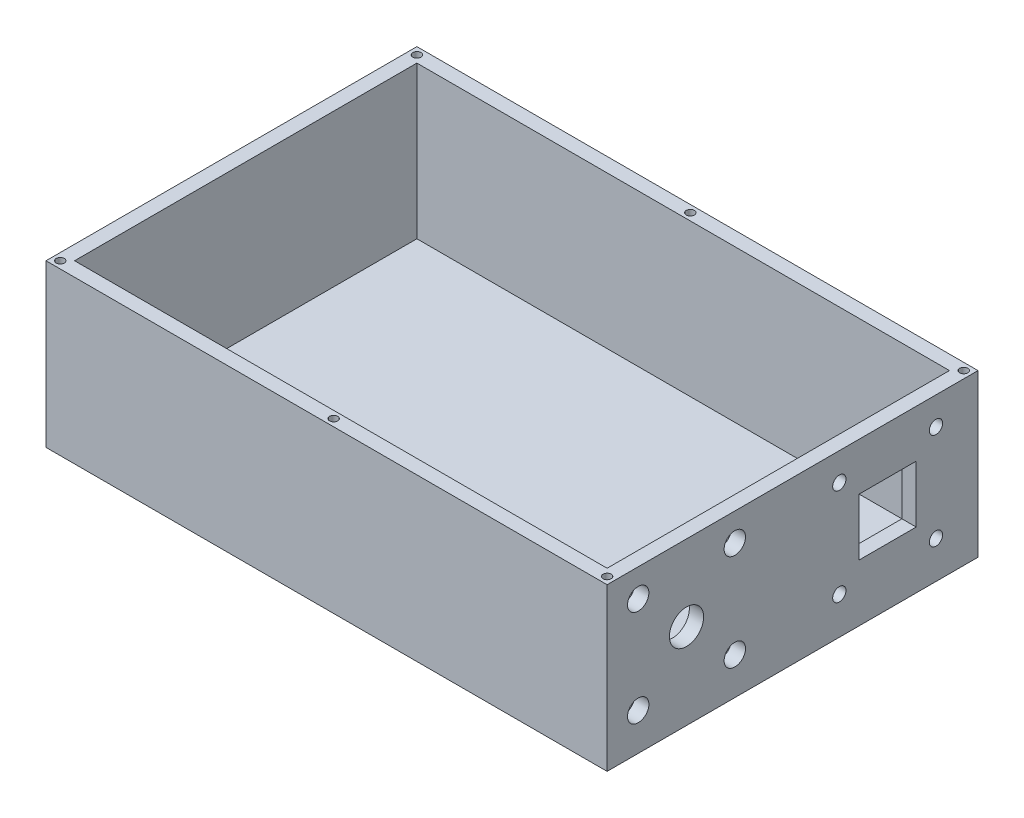
SolidWorks part; units mm, degrees
ref_plane "Front Plane" through (0, 0, 0) normal (0, 0, 1) x (1, 0, 0)
ref_plane "Top Plane" through (0, 0, 0) normal (0, 1, 0) x (1, 0, 0)
ref_plane "Right Plane" through (0, 0, 0) normal (1, 0, 0) x (0, 0, -1)
sketch "Sketch1" plane through (0, 0, 0) normal (0, 1, 0) x (1, 0, 0)
  line L1 (-59, 39) -> (59, 39)
  line L2 (-59, 39) -> (-59, -39)
  line L3 (-59, -39) -> (59, -39)
  line L4 (59, 39) -> (59, -39)
  line L5 (-59, 39) -> (59, -39) construction
  line L6 (-59, -39) -> (59, 39) construction
  point P0 (0, 0)
  dimension "D1" = 78
  dimension "D2" = 118
extrude "Main Box Up" add sketch "Sketch1" along normal blind 34
sketch "Sketch2" plane through (0, 34, 0) normal (0, 1, 0) x (1, 0, 0)
  line L1 (-56, 36) -> (56, 36)
  line L2 (-56, 36) -> (-56, -36)
  line L3 (-56, -36) -> (56, -36)
  line L4 (56, 36) -> (56, -36)
  line L5 (-56, 36) -> (56, -36) construction
  line L6 (-56, -36) -> (56, 36) construction
  point P0 (0, 0)
  dimension "D1" = 72
  dimension "D2" = 112
extrude "Main Box Into" cut sketch "Sketch2" against normal blind 32
sketch "Sketch4" plane through (56, 0, 0) normal (-1, 0, 0) x (0, 0, 1)
  line L0 (-20, 34) -> (-20, 2) construction
  line L1 (-32.7, 30.7) -> (-7.3, 30.7) construction
  line L2 (-32.7, 30.7) -> (-32.7, 5.3) construction
  line L3 (-32.7, 5.3) -> (-7.3, 5.3) construction
  line L4 (-7.3, 30.7) -> (-7.3, 5.3) construction
  line L5 (-32.7, 30.7) -> (-7.3, 5.3) construction
  line L6 (-32.7, 5.3) -> (-7.3, 30.7) construction
  line L7 (36, 34) -> (-36, 34) construction
  line L8 (36, 2) -> (-36, 2) construction
  line L9 (-36, 2) -> (-36, 34) construction
  line L11 (-26, 24) -> (-14, 24)
  line L12 (-26, 24) -> (-26, 12)
  line L13 (-26, 12) -> (-14, 12)
  line L14 (-14, 24) -> (-14, 12)
  line L15 (-26, 24) -> (-14, 12) construction
  line L16 (-26, 12) -> (-14, 24) construction
  line L17 (-30.16, 28.16) -> (-9.84, 28.16) construction
  line L18 (-30.16, 28.16) -> (-30.16, 7.84) construction
  line L19 (-30.16, 7.84) -> (-9.84, 7.84) construction
  line L20 (-9.84, 28.16) -> (-9.84, 7.84) construction
  line L21 (-30.16, 28.16) -> (-9.84, 7.84) construction
  line L22 (-30.16, 7.84) -> (-9.84, 28.16) construction
  circle A1 centre (-30.16, 28.16) radius 1.4
  circle A2 centre (-9.84, 28.16) radius 1.4
  circle A3 centre (-30.16, 7.84) radius 1.4
  circle A4 centre (-9.84, 7.84) radius 1.4
  point P0 (-20, 18)
  point P12 (-20, 18)
  point P15 (-20, 18)
  point P21 (-20, 18)
  dimension "D5" = 20.32
  dimension "D6" = 2.8
  dimension "D1" = 25.4
  dimension "D2" = 25.4
  dimension "D3" = 3.3
  dimension "D4" = 12
extrude "GPS" cut sketch "Sketch4" against normal blind 3
sketch "Sketch5" plane through (56, 0, 0) normal (-1, 0, 0) x (0, 0, 1)
  line L0 (22.3, 34) -> (22.3, 2) construction
  line L1 (9.6, 30.7) -> (35, 30.7) construction
  line L2 (9.6, 30.7) -> (9.6, 5.3) construction
  line L3 (9.6, 5.3) -> (35, 5.3) construction
  line L4 (35, 30.7) -> (35, 5.3) construction
  line L5 (9.6, 30.7) -> (35, 5.3) construction
  line L6 (9.6, 5.3) -> (35, 30.7) construction
  line L7 (36, 34) -> (-36, 34) construction
  line L8 (36, 2) -> (-36, 2) construction
  line L9 (36, 2) -> (36, 34) construction
  line L11 (12.14, 28.16) -> (32.46, 28.16) construction
  line L12 (12.14, 28.16) -> (12.14, 7.84) construction
  line L13 (12.14, 7.84) -> (32.46, 7.84) construction
  line L14 (32.46, 28.16) -> (32.46, 7.84) construction
  line L15 (12.14, 28.16) -> (32.46, 7.84) construction
  line L16 (12.14, 7.84) -> (32.46, 28.16) construction
  circle A0 centre (12.14, 28.16) radius 2.25
  circle A1 centre (32.46, 28.16) radius 2.25
  circle A2 centre (12.14, 7.84) radius 2.25
  circle A3 centre (32.46, 7.84) radius 2.25
  circle A4 centre (22.3, 18) radius 3.6
  point P0 (22.3, 18)
  point P12 (22.3, 18)
  point P15 (22.3, 18)
  dimension "D6" = 4.5
  dimension "D7" = 7.2
  dimension "D1" = 25.4
  dimension "D2" = 25.4
  dimension "D3" = 1
  dimension "D4" = 20.32
  dimension "D5" = 20.32
extrude "Cut-Extrude3" cut sketch "Sketch5" against normal blind 3
sketch "Sketch6" plane through (0, 34, 0) normal (0, 1, 0) x (1, 0, 0)
  line L0 (-59, 39) -> (-59, -39) construction
  line L1 (-57.5, 37.5) -> (57.5, 37.5) construction
  line L2 (-57.5, 37.5) -> (-57.5, -37.5) construction
  line L3 (-57.5, -37.5) -> (57.5, -37.5) construction
  line L4 (57.5, 37.5) -> (57.5, -37.5) construction
  line L5 (-57.5, 37.5) -> (57.5, -37.5) construction
  line L6 (-57.5, -37.5) -> (57.5, 37.5) construction
  line L7 (59, 39) -> (-59, 39) construction
  circle A0 centre (-57.5, 37.5) radius 0.85
  circle A1 centre (-57.5, -37.5) radius 0.85
  circle A2 centre (57.5, -37.5) radius 0.85
  circle A3 centre (57.5, 37.5) radius 0.85
  circle A4 centre (0, 37.5) radius 0.85
  circle A5 centre (0, -37.5) radius 0.85
  point P0 (0, 0)
  dimension "D3" = 1.7
  dimension "D1" = 1.5
  dimension "D2" = 1.5
extrude "Cut-Extrude4" cut sketch "Sketch6" against normal blind 4
